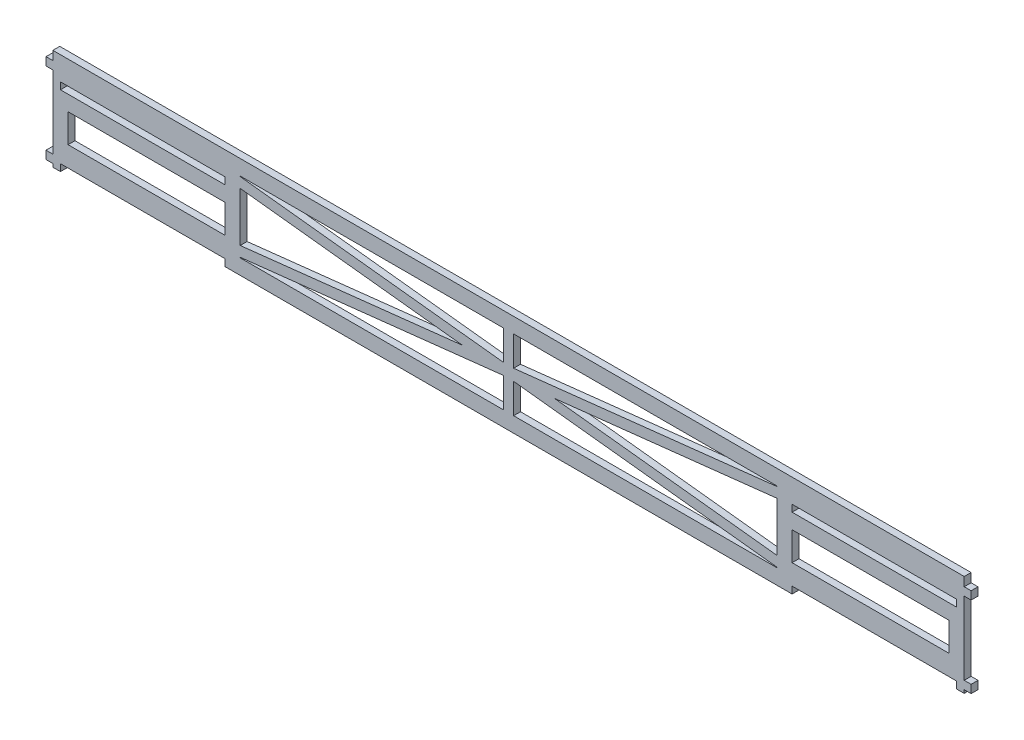
SolidWorks part; units mm, degrees
material "Delrin 2700 NC010, Low Viscosity Acetal Copolymer (SS)"
ref_plane "Front Plane" through (0, 0, 0) normal (0, 0, 1) x (1, 0, 0)
ref_plane "Top Plane" through (0, 0, 0) normal (0, 1, 0) x (1, 0, 0)
ref_plane "Right Plane" through (0, 0, 0) normal (1, 0, 0) x (0, 0, -1)
ref_plane "Horiz centerline" through (0, 0, 0) normal (0, 1, 0) x (-1, 0, 0)
ref_plane "Vertical plane" through (0, 0, 0) normal (1, 0, 0) x (0, 0, -1)
sketch "Sketch1" plane through (0, 0, 0) normal (0, 0, 1) x (1, 0, 0)
  line L0 (67.31, -6.2011) -> (11.5003, 0)
  line L1 (-112.395, -12.7) -> (-114.3, -12.7)
  line L2 (114.3, -12.7) -> (114.3, -11.8872)
  line L3 (114.3, 12.7) -> (-114.3, 12.7)
  line L4 (-114.3, -12.7) -> (-114.3, -11.8872)
  line L5 (114.3, -12.7) -> (-114.3, 12.7) construction
  line L6 (114.3, 12.7) -> (-114.3, -12.7) construction
  line L7 (-67.31, 8.89) -> (-1.27, 8.89)
  line L8 (-67.31, 8.89) -> (-67.31, 8.7567)
  line L9 (-67.31, -8.89) -> (-1.27, -8.89)
  line L10 (67.31, 8.89) -> (67.31, 8.7567)
  line L11 (-67.31, 8.89) -> (67.31, -8.89) construction
  line L12 (-67.31, -8.89) -> (67.31, 8.89) construction
  line L13 (67.31, -8.7567) -> (1.27, -1.4189)
  line L14 (67.31, 8.7567) -> (1.27, 1.4189)
  line L15 (67.31, 6.2011) -> (11.5003, 0)
  line L16 (114.4402, 11.4378) -> (-114.1598, -13.9622) construction
  line L17 (114.1598, 13.9622) -> (-114.4402, -11.4378) construction
  line L18 (-67.31, -8.7567) -> (-67.31, -8.89)
  line L19 (114.4402, -11.4378) -> (-114.1598, 13.9622) construction
  line L20 (114.1598, -13.9622) -> (-114.4402, 11.4378) construction
  line L21 (-67.31, 6.2011) -> (-67.31, -6.2011)
  line L22 (67.31, -8.7567) -> (67.31, -8.89)
  line L23 (67.31, 6.2011) -> (67.31, -6.2011)
  line L24 (-1.27, 1.4189) -> (-67.31, 8.7567)
  line L25 (-1.27, -1.4189) -> (-67.31, -8.7567)
  line L26 (-11.5003, 0) -> (-67.31, 6.2011)
  line L27 (-11.5003, 0) -> (-67.31, -6.2011)
  line L28 (-1.27, 8.89) -> (-1.27, 1.4189)
  line L29 (0, -55) -> (0, 55) construction
  line L30 (0, -1000) -> (0, 49000) construction
  line L31 (1.27, 8.89) -> (1.27, 1.4189)
  line L32 (-1.27, -1.4189) -> (-1.27, -8.89)
  line L33 (1.27, -1.4189) -> (1.27, -8.89)
  line L34 (1.27, -8.89) -> (67.31, -8.89)
  line L35 (1.27, 8.89) -> (67.31, 8.89)
  line L36 (-112.395, 6.8072) -> (-71.12, 6.8072)
  line L37 (-112.395, 6.8072) -> (-112.395, 5.08)
  line L38 (-112.395, 5.08) -> (-71.12, 5.08)
  line L39 (-71.12, 6.8072) -> (-71.12, 5.08)
  line L40 (71.12, 6.8072) -> (71.12, 5.08)
  line L41 (112.395, 5.08) -> (71.12, 5.08)
  line L42 (112.395, 6.8072) -> (112.395, 5.08)
  line L43 (112.395, 6.8072) -> (71.12, 6.8072)
  line L44 (71.12, -10.9728) -> (71.12, -12.7)
  line L45 (-112.395, -10.9728) -> (-71.12, -10.9728)
  line L46 (-112.395, -10.9728) -> (-112.395, -12.7)
  line L47 (71.12, -12.7) -> (-71.12, -12.7)
  line L48 (-71.12, -10.9728) -> (-71.12, -12.7)
  line L49 (110.49, 1.27) -> (110.49, -5.8928)
  line L50 (112.395, -10.9728) -> (112.395, -12.7)
  line L51 (112.395, -10.9728) -> (71.12, -10.9728)
  line L52 (114.3, -12.7) -> (112.395, -12.7)
  line L53 (-71.12, 1.27) -> (-110.49, 1.27)
  line L54 (-71.12, 1.27) -> (-71.12, -5.8928)
  line L55 (-71.12, -5.8928) -> (-110.49, -5.8928)
  line L56 (-110.49, 1.27) -> (-110.49, -5.8928)
  line L57 (71.12, -5.8928) -> (110.49, -5.8928)
  line L58 (71.12, 1.27) -> (71.12, -5.8928)
  line L59 (71.12, 1.27) -> (110.49, 1.27)
  line L64 (-116.0272, 10.4648) -> (-116.0272, 8.4328)
  line L65 (-114.3, -9.8552) -> (-116.0272, -9.8552)
  line L66 (-114.3, 10.4648) -> (-114.3, 12.7)
  line L67 (-114.3, -11.8872) -> (-116.0272, -11.8872)
  line L68 (-116.0272, -9.8552) -> (-116.0272, -11.8872)
  line L69 (-114.3, 8.4328) -> (-116.0272, 8.4328)
  line L70 (-114.3, 10.4648) -> (-116.0272, 10.4648)
  line L71 (114.3, -9.8552) -> (116.0272, -9.8552)
  line L72 (116.0272, -9.8552) -> (116.0272, -11.8872)
  line L73 (114.3, -11.8872) -> (116.0272, -11.8872)
  line L74 (114.3, 8.4328) -> (116.0272, 8.4328)
  line L75 (114.3, 10.4648) -> (116.0272, 10.4648)
  line L76 (116.0272, 10.4648) -> (116.0272, 8.4328)
  line L77 (114.3, 10.4648) -> (114.3, 12.7)
  line L78 (114.3, -9.8552) -> (114.3, 8.4328)
  line L79 (-114.3, -9.8552) -> (-114.3, 8.4328)
  point P0 (0, 0)
  point P5 (0, 0)
  dimension "D4" = 17.78
  dimension "D7" = 1.27
  dimension "D9" = 1.27
  dimension "D13" = 3.81
  dimension "D1" = 228.6
  dimension "D2" = 25.4
  dimension "D5" = 1.27
  dimension "D6" = 1.27
  dimension "D8" = 1.27
  dimension "D10" = 41.275
  dimension "D11" = 1.7272
  dimension "D12" = 1.905
  dimension "D15" = 1.7272
  dimension "D16" = 1.905
  dimension "D17" = 41.275
  dimension "D18" = 5.08
  dimension "D14" = 17.78
  dimension "D19" = 3.81
  dimension "D20" = 3.81
  dimension "D3" = 134.62
  dimension "D23" = 2.032
  dimension "D24" = 1.7272
  dimension "D26" = 2
extrude "Boss-Extrude1" add sketch "Sketch1" along normal blind 1.7272
